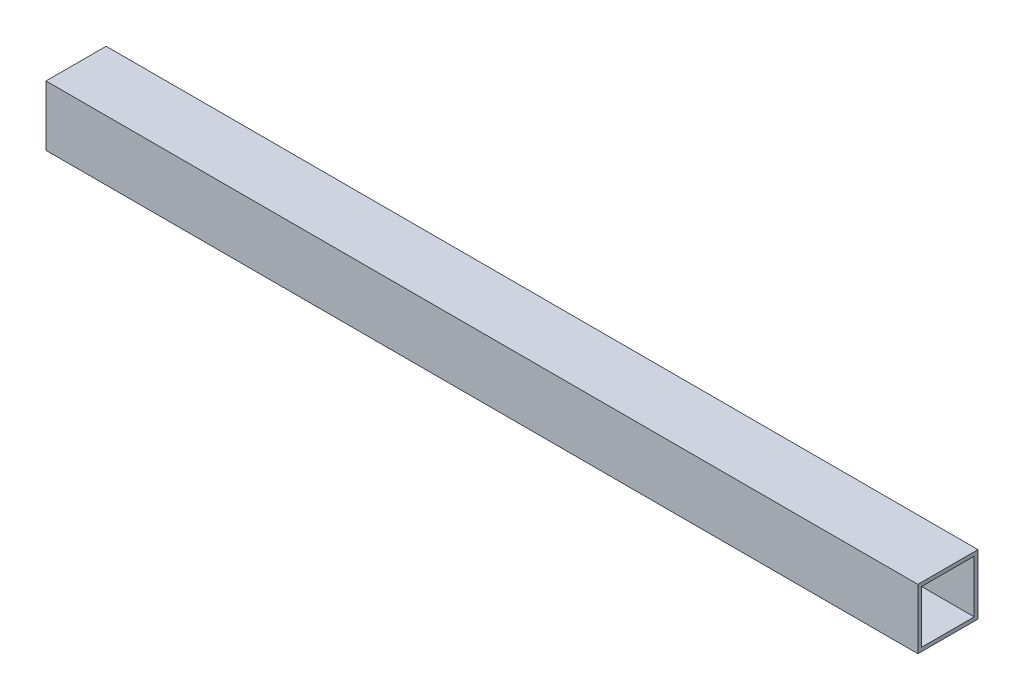
SolidWorks part; units mm, degrees
ref_plane "Front Plane" through (0, 0, 0) normal (0, 0, 1) x (1, 0, 0)
ref_plane "Top Plane" through (0, 0, 0) normal (0, 1, 0) x (1, 0, 0)
ref_plane "Right Plane" through (0, 0, 0) normal (1, 0, 0) x (0, 0, -1)
sketch "Sketch1" plane through (0, 0, 0) normal (1, 0, 0) x (0, 0, -1)
  line L1 (-12.7, -12.7) -> (12.7, -12.7)
  line L2 (-12.7, -12.7) -> (-12.7, 12.7)
  line L3 (-12.7, 12.7) -> (12.7, 12.7)
  line L4 (12.7, -12.7) -> (12.7, 12.7)
  line L5 (-12.7, -12.7) -> (12.7, 12.7) construction
  line L6 (-12.7, 12.7) -> (12.7, -12.7) construction
  line L7 (-11.1125, -11.1125) -> (11.1125, -11.1125)
  line L8 (-11.1125, -11.1125) -> (-11.1125, 11.1125)
  line L9 (-11.1125, 11.1125) -> (11.1125, 11.1125)
  line L10 (11.1125, -11.1125) -> (11.1125, 11.1125)
  line L11 (-11.1125, -11.1125) -> (11.1125, 11.1125) construction
  line L12 (-11.1125, 11.1125) -> (11.1125, -11.1125) construction
  point P0 (0, 0)
  point P6 (0, 0)
  dimension "D1" = 25.4
  dimension "D2" = 1.5875
extrude "Boss-Extrude1" add sketch "Sketch1" along normal blind 368.3
